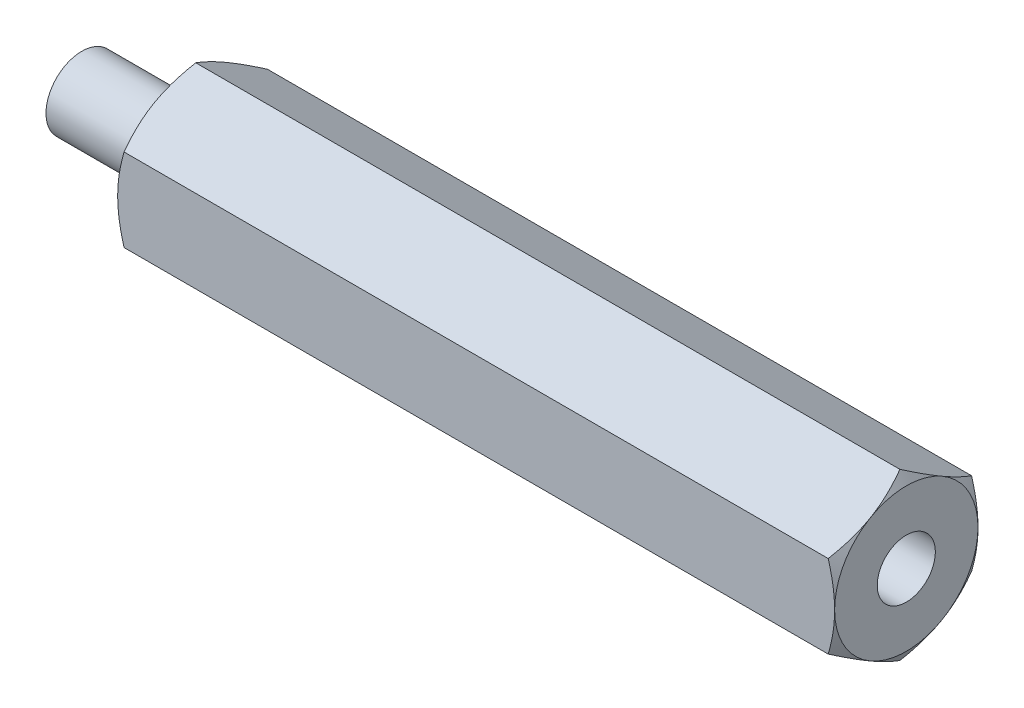
SolidWorks part; units mm, degrees
material "SUS304"
ref_plane "Front Plane" through (0, 0, 0) normal (0, 0, 1) x (1, 0, 0)
ref_plane "Top Plane" through (0, 0, 0) normal (0, 1, 0) x (1, 0, 0)
ref_plane "Right Plane" through (0, 0, 0) normal (1, 0, 0) x (0, 0, -1)
sketch "Sketch1" plane through (0, 0, 0) normal (1, 0, 0) x (0, 0, -1)
  line L1 (0, 4.6188) -> (-4, 2.3094)
  line L2 (-4, 2.3094) -> (-4, -2.3094)
  line L3 (-4, -2.3094) -> (0, -4.6188)
  line L4 (0, -4.6188) -> (4, -2.3094)
  line L5 (4, -2.3094) -> (4, 2.3094)
  line L6 (4, 2.3094) -> (0, 4.6188)
  circle A0 centre (0, 0) radius 4 construction
  dimension "C" = 9.2376
  dimension "B" = 8
extrude "Boss-Extrude1" add sketch "Sketch1" along normal blind 40
sketch "Sketch2" plane through (0, 0, 0) normal (0, 0, 1) x (1, 0, 0)
  line L0 (0, 0) -> (40, 0) construction
  line L1 (40, 2.3094) -> (40, -2.3094) construction
  line L2 (0, 4.6188) -> (0, 4)
  line L3 (0, 4) -> (0.3573, 4.6188)
  line L4 (0.3573, 4.6188) -> (0, 4.6188)
  line L5 (39.6427, 4.6188) -> (40, 4.6188)
  line L6 (40, 4.6188) -> (40, 4)
  line L7 (40, 4) -> (39.6427, 4.6188)
  line L8 (40, 4.6188) -> (0, 4.6188) construction
  line L9 (0, 4.6188) -> (0, 2.3094) construction
  line L10 (40, 4.6188) -> (40, 2.3094) construction
  dimension "FIX_1" = 30
revolve "Cut-Revolve1" cut sketch "Sketch2" angle 360 about L0
sketch "Sketch3" [suppressed] plane through (0, 0, 0) normal (0, 0, 1) x (1, 0, 0)
  line L0 (0, 0) -> (-4.5, 0) construction
  line L1 (0, 0) -> (0, 1.15)
  line L2 (0, 1.15) -> (-1, 1.15)
  line L3 (-1, 1.15) -> (-1, 1.5)
  line L4 (-1, 1.5) -> (-4.5, 1.5)
  line L5 (-4.5, 1.5) -> (-4.5, 0)
  line L6 (-4.5, 0) -> (0, 0)
  dimension "G_s" = 1.2
  dimension "MC" = 3.2
  dimension "M" = 4
  dimension "Mx1.5" = 6
revolve "Revolve1" [suppressed] add sketch "Sketch3" angle 360 about L0
cosmetic thread "Thread2" [suppressed]
hole_wizard "Tap1" [suppressed] positions "Sketch5" profile "Sketch4" hole size "M3x0.5" standard "JIS"
sketch "Sketch5" [suppressed] plane through (15, 0, 0) normal (1, 0, 0) x (0, 0, -1)
  point P0 (0, 0)
sketch "Sketch4" [suppressed] plane through (15, 0, 0) normal (0, 1, 0) x (0, 0, -1)
  line L0 (0, 0) -> (0, 8.2388)
  line L1 (0, 8.2388) -> (1.2295, 7.5)
  line L2 (1.2295, 7.5) -> (1.2295, 0)
  line L5 (1.2295, 0) -> (0, 0)
  line L10 (0, 8.2388) -> (-1.2295, 7.5) construction
  line L11 (0, 0) -> (0, 8.2388) construction
  dimension "Drill Angle" = 118
  dimension "HSL_1" = 10.1
cosmetic thread "Thread1" [suppressed]
ref_plane "Dim_M" through (4, 0, 0) normal (-1, 0, 0) x (0, 0, 1)
sketch "Sketch6" [suppressed] plane through (0, 0, 0) normal (0, 0, 1) x (1, 0, 0)
  line L0 (0, 0) -> (-4.5, 0) construction
  line L1 (0, 0) -> (0, 1.15)
  line L2 (0, 1.15) -> (-1, 1.15)
  line L3 (-1, 1.15) -> (-1, 1.5)
  line L4 (-1, 1.5) -> (-4.5, 1.5)
  line L5 (-4.5, 1.5) -> (-4.5, 0)
  line L6 (-4.5, 0) -> (0, 0)
  line L7 (0, 3.4641) -> (0, 3) construction
  dimension "G_s" = 1.2
  dimension "MC" = 3.2
  dimension "M" = 4
  dimension "Mx1.5" = 6
revolve "Revolve2" [suppressed] add sketch "Sketch6" angle 360 about L0
cosmetic thread "Thread3" [suppressed]
hole_wizard "Tap2" [suppressed] positions "Sketch8" profile "Sketch7" hole size "M3x0.5" standard "JIS"
sketch "Sketch8" [suppressed] plane through (15, 0, 0) normal (1, 0, 0) x (0, 0, -1)
  point P0 (0, 0)
sketch "Sketch7" [suppressed] plane through (15, 0, 0) normal (0, 1, 0) x (0, 0, -1)
  line L0 (0, 0) -> (0, 8.2388)
  line L1 (0, 8.2388) -> (1.2295, 7.5)
  line L2 (1.2295, 7.5) -> (1.2295, 0)
  line L5 (1.2295, 0) -> (0, 0)
  line L10 (0, 8.2388) -> (-1.2295, 7.5) construction
  line L11 (0, 0) -> (0, 8.2388) construction
  dimension "Drill Angle" = 118
  dimension "HSL_2" = 10.1
cosmetic thread "Thread4" [suppressed]
hole_wizard "Tap3" [suppressed] positions "Sketch10" profile "Sketch9" hole size "M2.5x0.45" standard "JIS"
sketch "Sketch10" [suppressed] plane through (15, 0, 0) normal (1, 0, 0) x (0, 0, -1)
  point P0 (0, 0)
sketch "Sketch9" [suppressed] plane through (15, 0, 0) normal (0, 1, 0) x (0, 0, -1)
  line L0 (0, 0) -> (0, 6.7388)
  line L1 (0, 6.7388) -> (1.2295, 6)
  line L2 (1.2295, 6) -> (1.2295, 0)
  line L5 (1.2295, 0) -> (0, 0)
  line L10 (0, 6.7388) -> (-1.2295, 6) construction
  line L11 (0, 0) -> (0, 6.7388) construction
  dimension "Drill Angle" = 118
  dimension "HSL_3" = 8.1
cosmetic thread "Thread5" [suppressed]
sketch "Sketch11" plane through (0, 0, 0) normal (0, 0, 1) x (1, 0, 0)
  line L0 (0, 0) -> (-6, 0) construction
  line L1 (0, 0) -> (0, 1.6)
  line L2 (0, 1.6) -> (-1.2, 1.6)
  line L3 (-1.2, 1.6) -> (-1.2, 2)
  line L4 (-1.2, 2) -> (-6, 2)
  line L5 (-6, 2) -> (-6, 0)
  line L6 (-6, 0) -> (0, 0)
  line L8 (0, 4.6188) -> (0, 4) construction
  dimension "G_s" = 1.2
  dimension "MC" = 3.2
  dimension "M" = 4
  dimension "Mx1.5" = 6
revolve "Revolve3" add sketch "Sketch11" angle 360 about L0
cosmetic thread "Thread6"
hole_wizard "Tap4" positions "Sketch13" profile "Sketch12" hole size "M3x0.5" standard "JIS"
sketch "Sketch13" plane through (40, 0, 0) normal (1, 0, 0) x (0, 0, -1)
  point P0 (0, 0)
sketch "Sketch12" plane through (40, 0, 0) normal (0, 1, 0) x (0, 0, -1)
  line L0 (0, 0) -> (0, 11.074)
  line L1 (0, 11.074) -> (1.621, 10.1)
  line L2 (1.621, 10.1) -> (1.621, 0)
  line L5 (1.621, 0) -> (0, 0)
  line L10 (0, 11.074) -> (-1.621, 10.1) construction
  line L11 (0, 0) -> (0, 11.074) construction
  dimension "Drill Angle" = 118
  dimension "HSL_4" = 10.1
cosmetic thread "Thread7"
hole_wizard "Tap5" [suppressed] positions "Sketch15" profile "Sketch14" hole size "M2.5x0.45" standard "JIS"
sketch "Sketch15" plane through (40, 0, 0) normal (1, 0, 0) x (0, 0, -1)
  point P0 (0, 0)
sketch "Sketch14" plane through (40, 0, 0) normal (0, 1, 0) x (0, 0, -1)
  line L0 (0, 0) -> (0, 9.074)
  line L1 (0, 9.074) -> (1.621, 8.1)
  line L2 (1.621, 8.1) -> (1.621, 0)
  line L5 (1.621, 0) -> (0, 0)
  line L10 (0, 9.074) -> (-1.621, 8.1) construction
  line L11 (0, -6.35) -> (0, 107.95) construction
  dimension "Drill Angle" = 118
  dimension "HSL_5" = 8.1
cosmetic thread "Thread8" [suppressed]
ref_plane "Dim_N" through (4, 0, 0) normal (-1, 0, 0) x (0, 0, 1)
sketch "Sketch16" [suppressed] plane through (0, 0, 0) normal (0, 0, 1) x (1, 0, 0)
  line L0 (-4.5, 0) -> (15, 0) construction
  line L1 (15, 3.4641) -> (15, 3) construction
  line L4 (-4.5, 0) -> (-4.5, 1.5) construction
  line L7 (-4.5, 0) -> (0, 0)
  line L8 (-4.5, 0) -> (-4.5, 1.5)
  line L9 (-4.5, 1.5) -> (0, 1.5)
  line L10 (0, 0) -> (0, 1.5)
  dimension "M" = 4
  dimension "Mx1.5" = 6
revolve "Cut-Revolve2" [suppressed] cut sketch "Sketch16" angle 360 about L0
sketch "Sketch17" [suppressed] plane through (0, 0, 0) normal (0, 0, 1) x (1, 0, 0)
  line L0 (0, 0) -> (-3, 0) construction
  line L1 (0, 0) -> (0, 1.15)
  line L2 (0, 1.15) -> (-1, 1.15)
  line L3 (-1, 1.15) -> (-1, 1.5)
  line L4 (-1, 1.5) -> (-3, 1.5)
  line L5 (-3, 1.5) -> (-3, 0)
  line L6 (-3, 0) -> (0, 0)
  dimension "G_s" = 1.2
  dimension "MC" = 3.2
  dimension "MLC" = 3
  dimension "M" = 4
revolve "Revolve4" [suppressed] add sketch "Sketch17" angle 360 about L0
cosmetic thread "Thread9" [suppressed]
hole_wizard "Tap6" [suppressed] positions "Sketch19" profile "Sketch18" hole size "M3x0.5" standard "JIS"
sketch "Sketch19" [suppressed] plane through (15, 0, 0) normal (1, 0, 0) x (0, 0, -1)
  point P0 (0, 0)
sketch "Sketch18" [suppressed] plane through (15, 0, 0) normal (0, 1, 0) x (0, 0, -1)
  line L0 (0, 0) -> (0, 11.2388)
  line L1 (0, 11.2388) -> (1.2295, 10.5)
  line L2 (1.2295, 10.5) -> (1.2295, 0)
  line L5 (1.2295, 0) -> (0, 0)
  line L10 (0, 11.2388) -> (-1.2295, 10.5) construction
  line L11 (0, 0) -> (0, 11.2388) construction
  dimension "Drill Angle" = 118
  dimension "HSL_6" = 14.1
cosmetic thread "Thread10" [suppressed]
equation "\"Mx2\"= \"M\" * 2"
equation "\"Factor\"= 1.082532"
equation "\"Pitch_M\"= IIF ( \"M\" = 24 , 3 , IIF ( \"M\" = 20 , 2.5 , IIF ( \"M\" = 16 , 2 , IIF ( \"M\" = 12 , 1.75 , IIF ( \"M\" = 10 , 1.5 , IIF ( \"M\" = 8 , 1.25 , IIF ( \"M\" = 6 , 1 , IIF ( \"M\" = 5 , 0.8 , IIF ( \"M\" = 4 , 0.7 , IIF ( \"M\" = 3 , 0.5 , IIF ( \"M\" = 2.6 , 0.45 , 0.4 ) ) ) ) ) ) ) ) ) ) )"
equation "\"HSD_1\"= round ( \"M\" - \"Factor\" * \"Pitch_M\" , 3 )"
equation "\"HSL_1\"= round ( \"Mx2\" + \"Pitch_M\" * 3 , 1 )"
equation "\"ATD_1\"= round ( \"M\" - \"Factor\" * \"Pitch_M\" , 3 )"
equation "\"Mx1.5\"= \"M\" * 1.5"
equation "\"ATD_2\"= round ( \"M\" - \"Factor\" * \"Pitch_M\" , 3 )"
equation "\"HSD_2\"= round ( \"M\" - \"Factor\" * \"Pitch_M\" , 3 )"
equation "\"HSL_2\"= round ( \"Mx2\" + \"Pitch_M\" * 3 , 1 )"
equation "\"HSD_3\"= round ( \"M\" - \"Factor\" * \"Pitch_M\" , 3 )"
equation "\"HSL_3\"= round ( \"Mx1.5\" + \"Pitch_M\" * 3 , 1 )"
equation "\"ATD_3\"= round ( \"M\" - \"Factor\" * \"Pitch_M\" , 3 )"
equation "\"Nx2\"= \"N\" * 2"
equation "\"Pitch_N\"= IIF ( \"N\" = 24 , 3 , IIF ( \"N\" = 20 , 2.5 , IIF ( \"N\" = 16 , 2 , IIF ( \"N\" = 12 , 1.75 , IIF ( \"N\" = 10 , 1.5 , IIF ( \"N\" = 8 , 1.25 , IIF ( \"N\" = 6 , 1 , IIF ( \"N\" = 5 , 0.8 , IIF ( \"N\" = 4 , 0.7 , IIF ( \"N\" = 3 , 0.5 , IIF ( \"N\" = 2.6 , 0.45 , 0.4 ) ) ) ) ) ) ) ) ) ) )"
equation "\"HSD_4\"= round ( \"N\" - \"Factor\" * \"Pitch_N\" , 3 )"
equation "\"HSL_4\"= round ( \"Nx2\" + \"Pitch_N\" * 3 , 1 )"
equation "\"Nx1.5\"= \"N\" * 1.5"
equation "\"HSD_5\"= round ( \"N\" - \"Factor\" * \"Pitch_N\" , 3 )"
equation "\"HSL_5\"= round ( \"Nx1.5\" + \"Pitch_N\" * 3 , 1 )"
equation "\"ATD_4\"= round ( \"M\" - \"Factor\" * \"Pitch_M\" , 3 )"
equation "\"Nx3\"= \"N\" * 3"
equation "\"HSD_6\"= round ( \"N\" - \"Factor\" * \"Pitch_N\" , 3 )"
equation "\"HSL_6\"= round ( \"Nx3\" + \"Pitch_N\" * 3 , 1 )"
